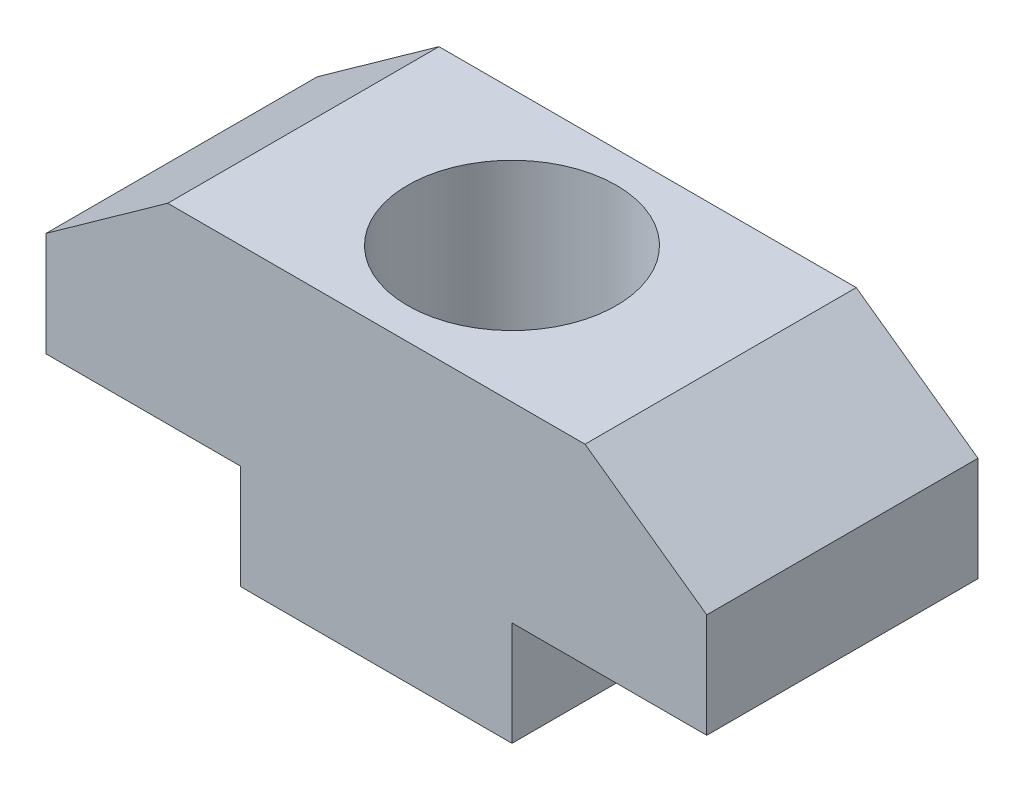
SolidWorks part; units mm, degrees
ref_plane "前视基准面" through (0, 0, 0) normal (0, 0, 1) x (1, 0, 0)
ref_plane "上视基准面" through (0, 0, 0) normal (0, 1, 0) x (1, 0, 0)
ref_plane "右视基准面" through (0, 0, 0) normal (1, 0, 0) x (0, 0, -1)
other "Configuration Table"
sketch "草图2" plane through (0, 0, 0) normal (0, 0, 1) x (1, 0, 0)
  line L0 (0, 0) -> (19, 0)
  line L1 (3.5, 5.5) -> (15.5, 5.5)
  line L2 (9.5, 0) -> (9.5, 7.2604) construction
  line L3 (0, 0) -> (0, 3)
  line L4 (19, 0) -> (19, 3)
  line L5 (0, 3) -> (3.5, 5.5)
  line L6 (15.5, 5.5) -> (19, 3)
  dimension "D1" = 19
  dimension "D2" = 5.5
  dimension "D3" = 12
  dimension "D4" = 6
  dimension "D5" = 3
  dimension "D6" = 3
extrude "凸台-拉伸2" add sketch "草图2" along normal blind 7.8
sketch "草图3" plane through (0, 0, 0) normal (0, -1, 0) x (-1, 0, 0)
  line L0 (-9.5, -7.8) -> (-9.5, 0) construction
  line L1 (0, -7.8) -> (-19, -7.8) construction
  line L2 (0, 0) -> (-19, 0) construction
  line L4 (-5.6, -7.8) -> (-13.4, -7.8)
  line L5 (-5.6, -7.8) -> (-5.6, 0)
  line L6 (-5.6, 0) -> (-13.4, 0)
  line L7 (-13.4, -7.8) -> (-13.4, 0)
  dimension "D1" = 7.8
  dimension "D2" = 3.9
extrude "凸台-拉伸3" add sketch "草图3" along normal blind 3
sketch "草图4" plane through (0, -3, 0) normal (0, -1, 0) x (-1, 0, 0)
  line L0 (-9.5, -7.8) -> (-9.5, 0) construction
  line L1 (-13.4, -7.8) -> (-5.6, -7.8) construction
  line L2 (-5.6, 0) -> (-13.4, 0) construction
  circle A0 centre (-9.5, -3.9) radius 3
  dimension "D1" = 6
extrude "切除-拉伸1" cut sketch "草图4" against normal up to next
cosmetic thread "装饰螺纹线1" parameters "D1"=5, "D2"=8
